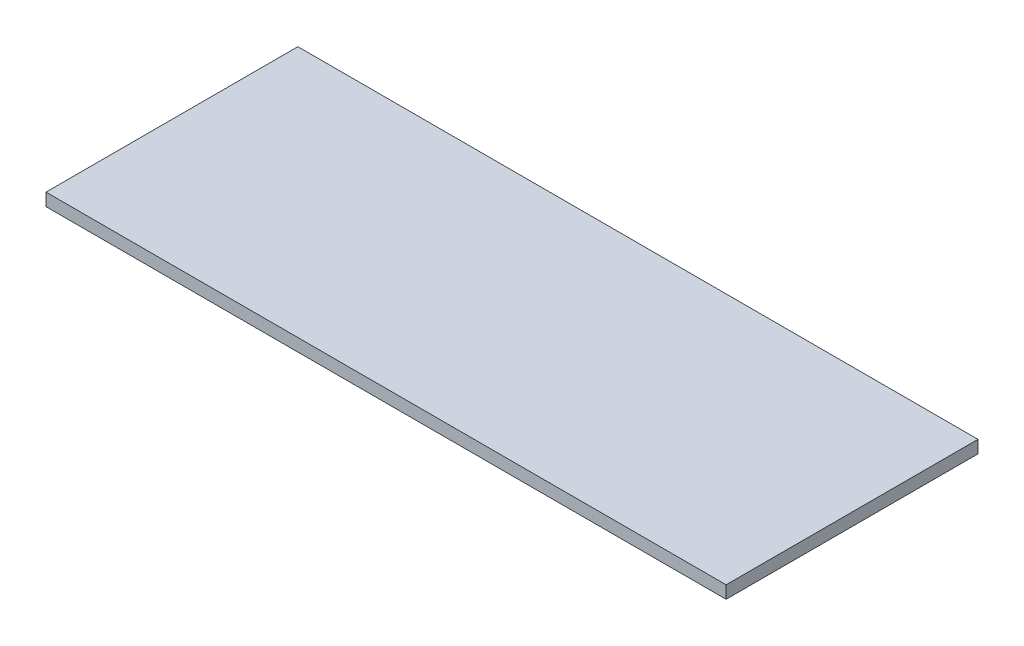
SolidWorks part; units mm, degrees
ref_plane "Front Plane" through (0, 0, 0) normal (0, 0, 1) x (1, 0, 0)
ref_plane "Top Plane" through (0, 0, 0) normal (0, 1, 0) x (1, 0, 0)
ref_plane "Right Plane" through (0, 0, 0) normal (1, 0, 0) x (0, 0, -1)
sketch "Sketch1" plane through (0, 0, 0) normal (0, 1, 0) x (1, 0, 0)
  line L1 (-81, 30) -> (81, 30)
  line L2 (-81, 30) -> (-81, -30)
  line L3 (-81, -30) -> (81, -30)
  line L4 (81, 30) -> (81, -30)
  line L5 (-81, 30) -> (81, -30) construction
  line L6 (-81, -30) -> (81, 30) construction
  point P0 (0, 0)
extrude "Boss-Extrude1" add sketch "Sketch1" along normal blind 3
